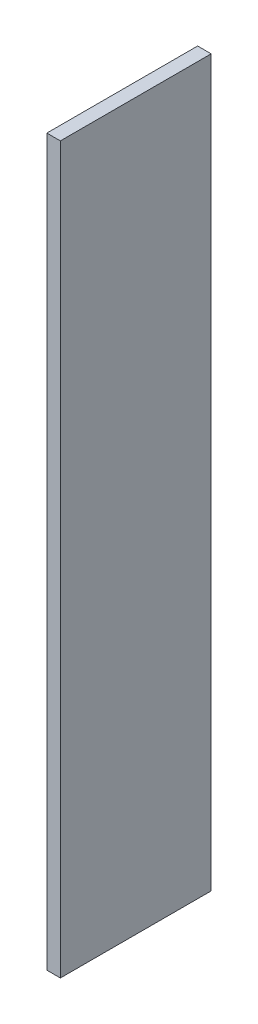
SolidWorks part; units mm, degrees
ref_plane "Front Plane" through (0, 0, 0) normal (0, 0, 1) x (1, 0, 0)
ref_plane "Top Plane" through (0, 0, 0) normal (0, 1, 0) x (1, 0, 0)
ref_plane "Right Plane" through (0, 0, 0) normal (1, 0, 0) x (0, 0, -1)
sketch "Sketch1" plane through (0, 0, 0) normal (1, 0, 0) x (0, 0, -1)
  line L1 (-7.8, -37.5) -> (7.8, -37.5)
  line L2 (-7.8, -37.5) -> (-7.8, 37.5)
  line L3 (-7.8, 37.5) -> (7.8, 37.5)
  line L4 (7.8, -37.5) -> (7.8, 37.5)
  line L5 (-7.8, -37.5) -> (7.8, 37.5) construction
  line L6 (-7.8, 37.5) -> (7.8, -37.5) construction
  point P0 (0, 0)
  dimension "D1" = 75
  dimension "D2" = 15.6
extrude "Boss-Extrude4" add sketch "Sketch1" along normal blind 1.4
